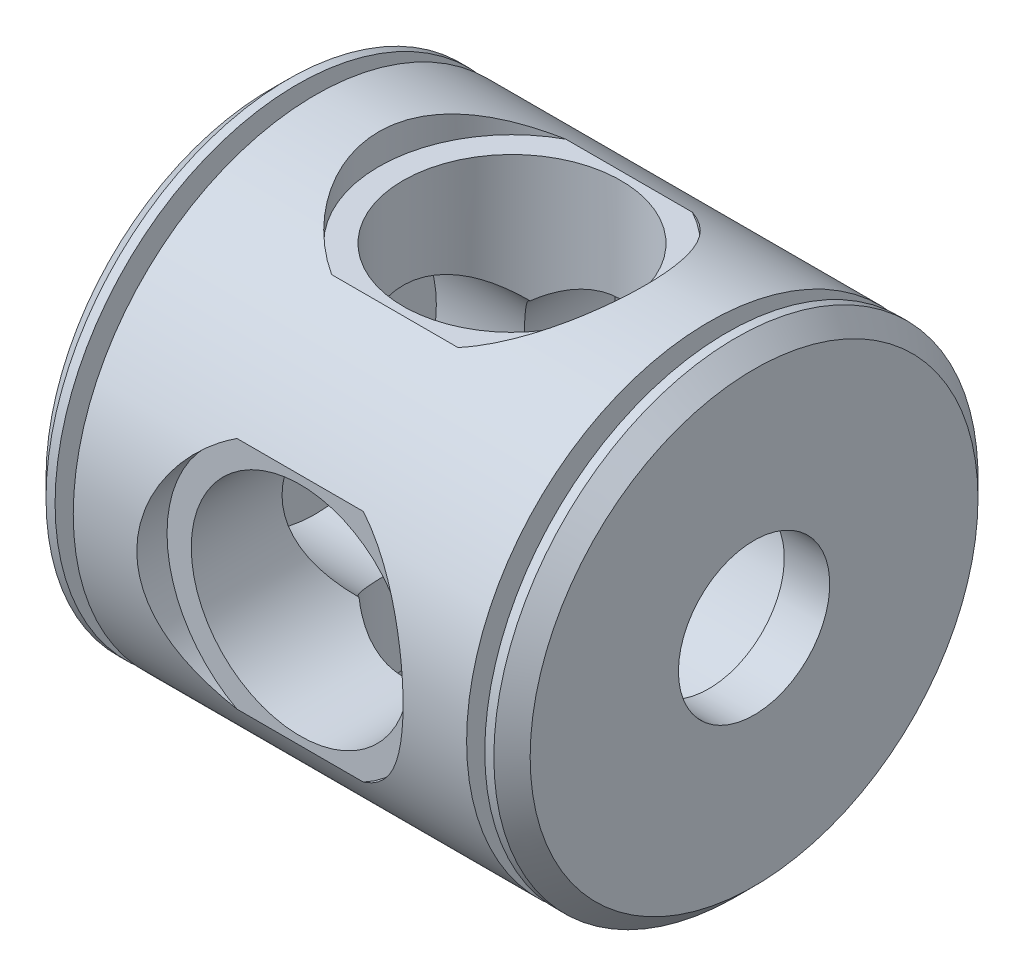
SolidWorks part; units mm, degrees
ref_plane "Front Plane" through (0, 0, 0) normal (0, 0, 1) x (1, 0, 0)
ref_plane "Top Plane" through (0, 0, 0) normal (0, 1, 0) x (1, 0, 0)
ref_plane "Right Plane" through (0, 0, 0) normal (1, 0, 0) x (0, 0, -1)
sketch "Sketch2" plane through (0, 0, 0) normal (0, 0, 1) x (1, 0, 0)
  line L0 (-15.7109, 0) -> (14.6801, 0) construction
  line L1 (32.5, 12.5) -> (40, 12.5)
  line L2 (40, 12.5) -> (40, 40)
  line L3 (40, 40) -> (35.5, 40)
  line L4 (35.5, 40) -> (35.5, 35)
  line L5 (35.5, 35) -> (32.5, 35)
  line L6 (32.5, 35) -> (32.5, 40)
  line L7 (32.5, 40) -> (0, 40)
  line L8 (0, 40) -> (0, 20)
  line L9 (0, 20) -> (32.5, 20)
  line L10 (32.5, 20) -> (32.5, 12.5)
  dimension "D1" = 7.5
  dimension "D2" = 40
  dimension "D3" = 7.5
  dimension "D4" = 3
  dimension "D5" = 7.5
  dimension "D6" = 5
  dimension "D7" = 12.5
  dimension "D8" = 40
revolve "Revolve1" add sketch "Sketch2" angle 360 about L0
chamfer "Chamfer1" distance 3 angle 45 1 edges at (40, 0, 40)
mirror "Mirror1" about plane through (0, 40, 0) normal (1, 0, 0) of "Chamfer1", "Revolve1"
ref_plane "Plane1" through (0, 0, -40) normal (0, 0, -1) x (-1, 0, 0)
sketch "Sketch3" plane through (0, 0, -40) normal (0, 0, -1) x (-1, 0, 0)
  circle A0 centre (0, 0) radius 22
  dimension "D1" = 44
extrude "Cut-Extrude1" cut sketch "Sketch3" against normal blind 5
sketch "Sketch4" plane through (0, 0, -35) normal (0, 0, -1) x (-1, 0, 0)
  circle A0 centre (0, 0) radius 18
  dimension "D1" = 36
extrude "Cut-Extrude3" cut sketch "Sketch4" against normal up to next
pattern_circular "CirPattern2" count 4 over 360 about axis through (0, 0, 0) along (1, 0, 0) of "Cut-Extrude3", "Cut-Extrude1"
